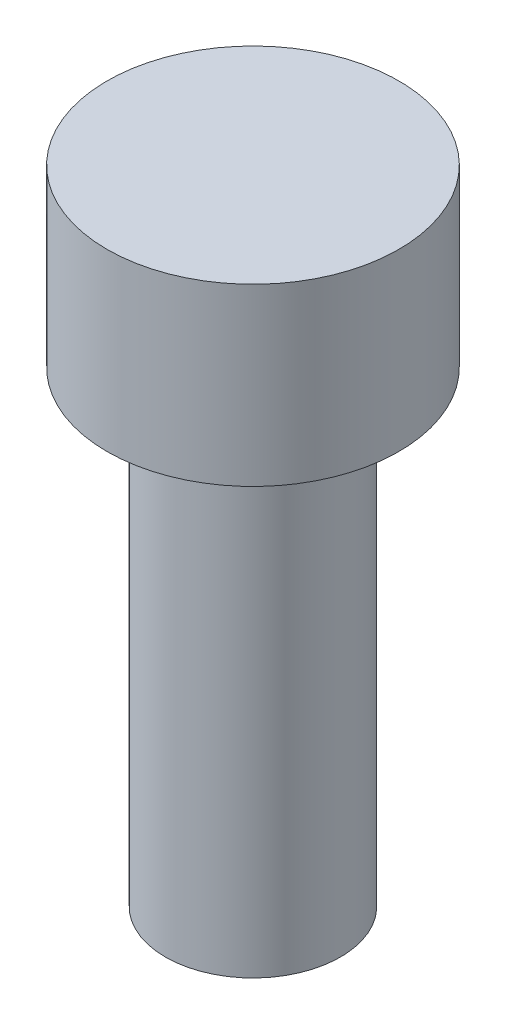
SolidWorks part; units mm, degrees
ref_plane "Front Plane" through (0, 0, 0) normal (0, 0, 1) x (1, 0, 0)
ref_plane "Top Plane" through (0, 0, 0) normal (0, 1, 0) x (1, 0, 0)
ref_plane "Right Plane" through (0, 0, 0) normal (1, 0, 0) x (0, 0, -1)
sketch "Sketch1" plane through (0, 0, 0) normal (1, 0, 0) x (0, 0, -1)
  line L0 (0, 22) -> (0, 0)
  line L1 (0, 0) -> (-3, 0)
  line L2 (-3, 0) -> (-3, 16)
  line L3 (-3, 16) -> (-5, 16)
  line L4 (-5, 16) -> (-5, 22)
  line L5 (-5, 22) -> (0, 22)
  dimension "D1" = 6
  dimension "D2" = 16
  dimension "D3" = 5
  dimension "D4" = 3
revolve "Revolve1" add sketch "Sketch1" angle 360 about L0
